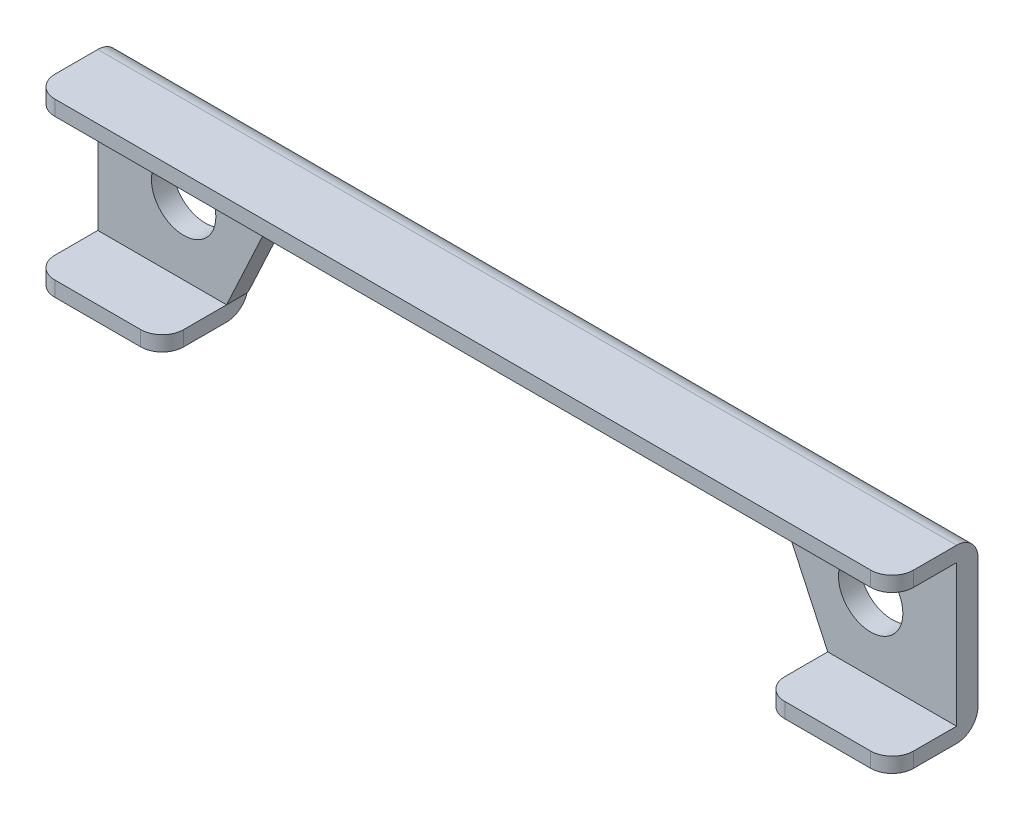
SolidWorks part; units mm, degrees
material "Cast Alloy Steel"
ref_plane "Front" through (0, 0, 0) normal (0, 0, 1) x (1, 0, 0)
ref_plane "Top" through (0, 0, 0) normal (0, 1, 0) x (1, 0, 0)
ref_plane "Right" through (0, 0, 0) normal (1, 0, 0) x (0, 0, -1)
sketch "Sketch1" plane through (0, 0, 0) normal (0, 0, 1) x (1, 0, 0)
  line L1 (-20, 4) -> (20, 4)
  line L2 (-20, 4) -> (-20, -4)
  line L3 (-20, -4) -> (20, -4)
  line L4 (20, 4) -> (20, -4)
  line L5 (-20, 4) -> (20, -4) construction
  line L6 (-20, -4) -> (20, 4) construction
  point P0 (0, 0)
  dimension "D1" = 8
  dimension "D2" = 40
extrude "Boss-Extrude1" add sketch "Sketch1" along normal blind 1
sketch "Sketch2" plane through (0, 0, 1) normal (0, 0, 1) x (1, 0, 0)
  line L0 (-12.5, 1) -> (12.5, 1)
  line L1 (20, 4) -> (-20, 4) construction
  line L2 (-14, -4) -> (14, -4)
  line L3 (-20, -4) -> (20, -4) construction
  line L4 (-20, 4) -> (-20, -4) construction
  line L5 (-14, -4) -> (-20, -4)
  line L6 (-14, -4) -> (-14, -3.3)
  line L7 (-14, -3.3) -> (-20, -3.3)
  line L8 (-20, -4) -> (-20, -3.3)
  line L9 (-17, -3.3) -> (-17, -4) construction
  line L10 (-14, -3.65) -> (-20, -3.65) construction
  line L11 (20, -4) -> (20, 4) construction
  line L12 (14, -4) -> (20, -4)
  line L13 (14, -4) -> (14, -3.3)
  line L14 (14, -3.3) -> (20, -3.3)
  line L15 (20, -4) -> (20, -3.3)
  line L16 (17, -3.3) -> (17, -4) construction
  line L17 (14, -3.65) -> (20, -3.65) construction
  line L18 (-14, -3.3) -> (-12.5, 1)
  line L19 (12.5, 1) -> (14, -3.3)
  point P4 (0, 1)
  point P11 (0, -4)
  point P88 (17, -3.65)
  point P123 (-17, -3.65)
  line M5 (20, -4) -> (20, 4)
  line M7 (-20, 4) -> (-20, -4)
  line M8 (-20, -4) -> (20, -4)
  dimension "D1" = 3
  dimension "D2" = 0
  dimension "D3" = 25
  dimension "D4" = 0
  dimension "D5" = 28
  dimension "D6" = 0.7
  dimension "D7" = 0.7
extrude "Boss-Extrude2" add sketch "Sketch2" along normal blind 3 contours L6 L7 M7 M8 | L14 L13 M8 M5
sketch "Sketch3" plane through (0, 0, 1) normal (0, 0, 1) x (1, 0, 0)
  line L0 (20, -3.3) -> (20, 4) construction
  line L1 (-20, 4) -> (20, 4)
  line L2 (-20, 4) -> (-20, 3.3)
  line L3 (-20, 3.3) -> (20, 3.3)
  line L4 (20, 4) -> (20, 3.3)
  line L5 (0, 3.3) -> (0, 4) construction
  line L6 (-20, 3.65) -> (20, 3.65) construction
  point P264 (0, 3.65)
  dimension "D1" = 0.7
extrude "Boss-Extrude3" add sketch "Sketch3" along normal blind 3
sketch "Sketch4" plane through (0, 0, 1) normal (0, 0, 1) x (1, 0, 0)
  line L0 (-12, 1) -> (12, 1)
  line L1 (20, 4) -> (-20, 4) construction
  line L2 (-12, 1) -> (-14, -3.3)
  line L3 (-14, -3.3) -> (-14, -4)
  line L4 (-14, -4) -> (14, -4)
  line L5 (14, -4) -> (14, -3.3)
  line L6 (14, -3.3) -> (12, 1)
  point P2 (0, 1)
  dimension "D1" = 0
  dimension "D2" = 24
  dimension "D3" = 3
extrude "Cut-Extrude2" cut sketch "Sketch4" against normal blind 3
sketch "Sketch5" plane through (0, 0, 1) normal (0, 0, 1) x (1, 0, 0)
  line L0 (20, -3.3) -> (20, 3.3) construction
  line L1 (-20, 3.3) -> (-20, -3.3) construction
  circle A0 centre (16, 0) radius 1.5
  circle A1 centre (-16, 0) radius 1.5
  dimension "D1" = 4
  dimension "D2" = 4
extrude "Cut-Extrude3" cut sketch "Sketch5" against normal blind 3
fillet "Fillet1" radius 1 9 edges at (-14, -3.65, 4) (-20, -3.65, 4) (14, -3.65, 4) (20, -3.65, 4) (20, 3.65, 4) (-20, 3.65, 4) (17, -4, 0) (-17, -4, 0) (0, 4, 0)
